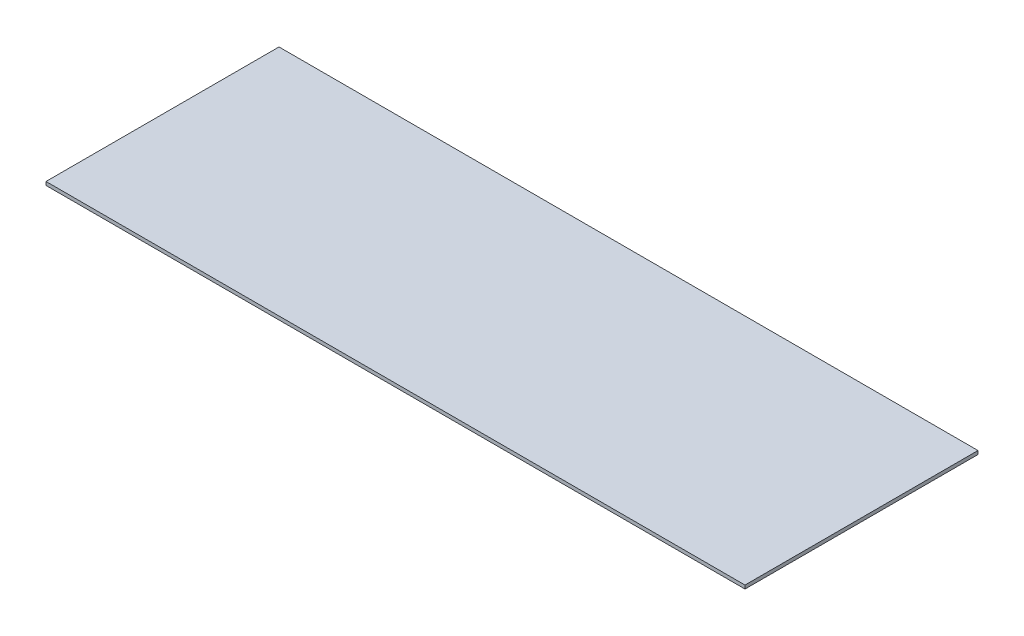
SolidWorks part; units mm, degrees
ref_plane "Front Plane" through (0, 0, 0) normal (0, 0, 1) x (1, 0, 0)
ref_plane "Top Plane" through (0, 0, 0) normal (0, 1, 0) x (1, 0, 0)
ref_plane "Right Plane" through (0, 0, 0) normal (1, 0, 0) x (0, 0, -1)
sketch "Sketch1" plane through (0, 0, 0) normal (0, 1, 0) x (1, 0, 0)
  line L1 (600, -200) -> (-600, -200)
  line L2 (600, -200) -> (600, 200)
  line L3 (600, 200) -> (-600, 200)
  line L4 (-600, -200) -> (-600, 200)
  line L5 (600, -200) -> (-600, 200) construction
  line L6 (600, 200) -> (-600, -200) construction
  point P0 (0, 0)
  dimension "D1" = 400
  dimension "D2" = 1200
extrude "Boss-Extrude1" add sketch "Sketch1" along normal blind 6
